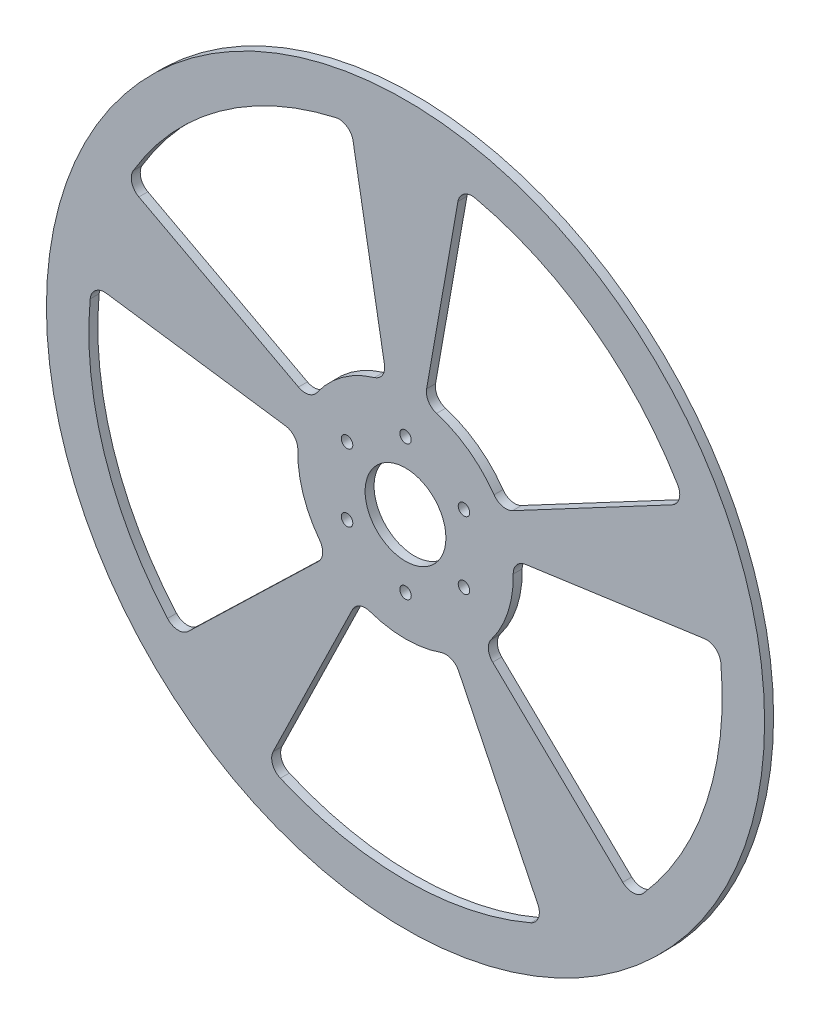
SolidWorks part; units mm, degrees
material "6061 Alloy"
ref_plane "Front Plane" through (0, 0, 0) normal (0, 0, 1) x (1, 0, 0)
ref_plane "Top Plane" through (0, 0, 0) normal (0, 1, 0) x (1, 0, 0)
ref_plane "Right Plane" through (0, 0, 0) normal (1, 0, 0) x (0, 0, -1)
sketch "Sketch1" plane through (0, 0, 0) normal (0, 0, 1) x (1, 0, 0)
  line L0 (0, 38.1) -> (0, 112) construction
  line L1 (36.2353, 11.7735) -> (106.5183, 34.6099) construction
  line L2 (65.8319, -90.6099) -> (22.3946, -30.8235) construction
  line L3 (-22.3946, -30.8235) -> (-65.8319, -90.6099) construction
  line L4 (-106.5183, 34.6099) -> (-36.2353, 11.7735) construction
  line L5 (19.4486, 110.2985) -> (6.616, 37.5212)
  line L6 (-6.616, 37.5212) -> (-19.4486, 110.2985)
  line L7 (33.6403, 17.8869) -> (98.8901, 52.5808)
  line L8 (37.7292, 5.3025) -> (110.91, 15.5874)
  line L9 (80.5661, -77.8017) -> (27.4068, -26.4665)
  line L10 (49.0976, -100.6649) -> (16.7019, -34.2441)
  line L11 (-49.0976, -100.6649) -> (-16.7019, -34.2441)
  line L12 (-80.5661, -77.8017) -> (-27.4068, -26.4665)
  line L13 (-98.8901, 52.5808) -> (-33.6403, 17.8869)
  line L14 (-110.91, 15.5874) -> (-37.7292, 5.3025)
  circle A1 centre (0, 0) radius 127
  circle A2 centre (0, 0) radius 112 construction
  circle A4 centre (0, 0) radius 38.1 construction
  arc A5 (-6.616, 37.5212) -> (-33.6403, 17.8869) centre (0, 0) ccw
  arc A6 (-37.7292, 5.3025) -> (-27.4068, -26.4665) centre (0, 0) ccw
  arc A7 (-16.7019, -34.2441) -> (16.7019, -34.2441) centre (0, 0) ccw
  arc A8 (27.4068, -26.4665) -> (37.7292, 5.3025) centre (0, 0) ccw
  arc A9 (33.6403, 17.8869) -> (6.616, 37.5212) centre (0, 0) ccw
  arc A10 (98.8901, 52.5808) -> (19.4486, 110.2985) centre (0, 0) ccw
  arc A11 (-19.4486, 110.2985) -> (-98.8901, 52.5808) centre (0, 0) ccw
  arc A12 (-110.91, 15.5874) -> (-80.5661, -77.8017) centre (0, 0) ccw
  arc A13 (-49.0976, -100.6649) -> (49.0976, -100.6649) centre (0, 0) ccw
  arc A14 (110.91, 15.5874) -> (80.5661, -77.8017) centre (0, 0) cw
  circle A15 centre (0, 0) radius 14.2875
  circle A16 centre (0, 23.876) radius 2.032
  circle A17 centre (20.6772, 11.938) radius 2.032
  circle A18 centre (20.6772, -11.938) radius 2.032
  circle A19 centre (0, -23.876) radius 2.032
  circle A20 centre (-20.6772, -11.938) radius 2.032
  circle A21 centre (-20.6772, 11.938) radius 2.032
  point P50 (0, 0)
  dimension "D3" = 15
  dimension "D4" = 76.2
  dimension "D6" = 72
  dimension "D19" = 28.575
  dimension "D21" = 4.064
  dimension "D23" = 254
  dimension "D5" = 72
  dimension "D7" = 72
  dimension "D8" = 72
  dimension "D9" = 20
  dimension "D10" = 10
  dimension "D11" = 10
  dimension "D12" = 20
  dimension "D13" = 10
  dimension "D14" = 20
  dimension "D15" = 10
  dimension "D16" = 20
  dimension "D17" = 10
  dimension "D18" = 20
  dimension "D20" = 23.876
  dimension "D22" = 6
extrude "Boss-Extrude2" add sketch "Sketch1" along normal blind 3.175
fillet "Fillet1" radius 5.08 4 edges at (98.8901, 52.5808, 1.5875) (33.6403, 17.8869, 1.5875) (6.616, 37.5212, 1.5875) (19.4486, 110.2985, 1.5875)
fillet "Fillet3" radius 5.08 16 edges at (37.7292, 5.3025, 1.5875) (27.4068, -26.4665, 1.5875) (80.5661, -77.8017, 1.5875) (110.91, 15.5874, 1.5875) (-49.0976, -100.6649, 1.5875) (49.0976, -100.6649, 1.5875) (16.7019, -34.2441, 1.5875) (-16.7019, -34.2441, 1.5875) (-80.5661, -77.8017, 1.5875) (-27.4068, -26.4665, 1.5875) (-37.7292, 5.3025, 1.5875) (-110.91, 15.5874, 1.5875) (-6.616, 37.5212, 1.5875) (-33.6403, 17.8869, 1.5875) (-98.8901, 52.5808, 1.5875) (-19.4486, 110.2985, 1.5875)
